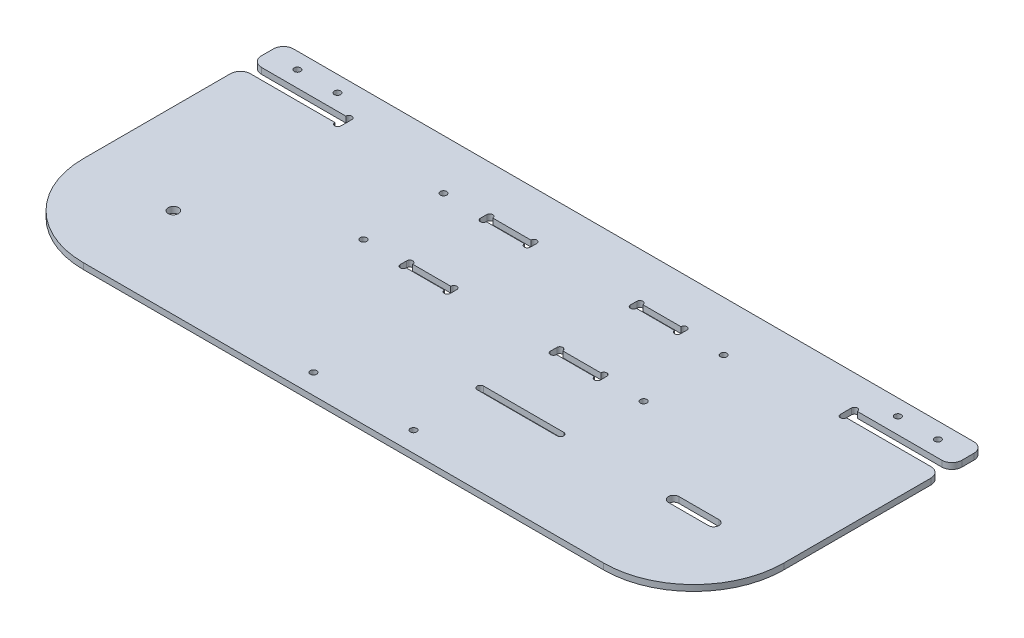
SolidWorks part; units mm, degrees
ref_plane "Front Plane" through (0, 0, 0) normal (0, 0, 1) x (1, 0, 0)
ref_plane "Top Plane" through (0, 0, 0) normal (0, 1, 0) x (1, 0, 0)
ref_plane "Right Plane" through (0, 0, 0) normal (1, 0, 0) x (0, 0, -1)
sketch "Sketch1" plane through (0, 0, 0) normal (0, 1, 0) x (1, 0, 0)
  line L0 (0, 0) -> (260, 0) construction
  line L5 (0, 45) -> (260, 45)
  line L6 (0, -45) -> (260, -45)
  line L7 (270, 0) -> (250, 0) construction
  line L8 (270, -2.6) -> (250, -2.6)
  line L9 (270, 2.6) -> (250, 2.6)
  line L11 (-45, 0) -> (305, 0) construction
  line L12 (-45, 0) -> (-45, 100)
  line L13 (-45, 100) -> (305, 100)
  line L14 (305, 0) -> (305, 100)
  arc A0 (0, 45) -> (0, -45) centre (0, 0) ccw
  arc A1 (260, -45) -> (260, 45) centre (260, 0) ccw
  circle A2 centre (0, 0) radius 2.6
  arc A4 (270, -2.6) -> (270, 2.6) centre (270, 0) ccw
  arc A5 (250, 2.6) -> (250, -2.6) centre (250, 0) ccw
  point P2 (130, 0)
  point P12 (260, 0)
  dimension "D2" = 45
  dimension "D3" = 5.2
  dimension "D1" = 260
  dimension "D4" = 20
  dimension "D5" = 100
  dimension "D6" = 270
extrude "Boss-Extrude1" add sketch "Sketch1" along normal blind 3 contours L6 A1 L5 A0 A5 L9 A4 L8 A2 | A1 L14 L13 L12 A0 L5
sketch "Sketch2" plane through (0, 0, 0) normal (0, -1, 0) x (1, 0, 0)
  line L0 (130, 45) -> (130, -100) construction
  line L1 (80, -73.4) -> (105, -73.4)
  line L2 (80, -73.4) -> (80, -76.6)
  line L3 (80, -76.6) -> (105, -76.6)
  line L4 (105, -73.4) -> (105, -76.6)
  line L5 (0, 45) -> (260, 45) construction
  line L6 (-45, -100) -> (305, -100) construction
  line L7 (-45, -75) -> (305, -75) construction
  line L8 (-45, 0) -> (-45, -100) construction
  line L9 (305, 0) -> (305, -100) construction
  line L10 (81.5, -73.4) -> (81.5, -76.6) construction
  line L11 (83, -73.4) -> (83, -76.6)
  line L12 (80, -73.4) -> (80, -76.6)
  line L13 (103.5, -73.4) -> (103.5, -76.6) construction
  line L14 (105, -73.4) -> (105, -76.6)
  line L15 (102, -73.4) -> (102, -76.6)
  line L16 (-45, -55) -> (305, -55) construction
  line L17 (156.5, -73.4) -> (156.5, -76.6) construction
  line L18 (155, -73.4) -> (155, -76.6)
  line L19 (158, -73.4) -> (158, -76.6)
  line L20 (180, -76.6) -> (155, -76.6)
  line L21 (180, -73.4) -> (155, -73.4)
  line L22 (178.5, -73.4) -> (178.5, -76.6) construction
  line L23 (177, -73.4) -> (177, -76.6)
  line L24 (180, -73.4) -> (180, -76.6)
  line L25 (180, -33.4) -> (155, -33.4)
  line L26 (81.5, -36.6) -> (81.5, -33.4) construction
  line L27 (83, -36.6) -> (83, -33.4)
  line L28 (80, -36.6) -> (80, -33.4)
  line L29 (80, -33.4) -> (105, -33.4)
  line L30 (103.5, -36.6) -> (103.5, -33.4) construction
  line L31 (105, -36.6) -> (105, -33.4)
  line L32 (102, -36.6) -> (102, -33.4)
  line L33 (80, -36.6) -> (105, -36.6)
  line L34 (156.5, -36.6) -> (156.5, -33.4) construction
  line L35 (155, -36.6) -> (155, -33.4)
  line L36 (158, -36.6) -> (158, -33.4)
  line L37 (180, -36.6) -> (155, -36.6)
  line L38 (178.5, -36.6) -> (178.5, -33.4) construction
  line L39 (177, -36.6) -> (177, -33.4)
  line L40 (180, -36.6) -> (180, -33.4)
  line L41 (-45, -92) -> (305, -92) construction
  arc A0 (83, -73.4) -> (80, -73.4) centre (81.5, -73.4) ccw
  arc A1 (80, -76.6) -> (83, -76.6) centre (81.5, -76.6) ccw
  arc A2 (105, -73.4) -> (102, -73.4) centre (103.5, -73.4) ccw
  arc A3 (102, -76.6) -> (105, -76.6) centre (103.5, -76.6) ccw
  arc A4 (155, -73.4) -> (158, -73.4) centre (156.5, -73.4) cw
  arc A5 (158, -76.6) -> (155, -76.6) centre (156.5, -76.6) cw
  arc A6 (177, -73.4) -> (180, -73.4) centre (178.5, -73.4) cw
  arc A7 (180, -76.6) -> (177, -76.6) centre (178.5, -76.6) cw
  arc A8 (83, -36.6) -> (80, -36.6) centre (81.5, -36.6) cw
  arc A9 (80, -33.4) -> (83, -33.4) centre (81.5, -33.4) cw
  arc A10 (105, -36.6) -> (102, -36.6) centre (103.5, -36.6) cw
  arc A11 (102, -33.4) -> (105, -33.4) centre (103.5, -33.4) cw
  arc A12 (155, -36.6) -> (158, -36.6) centre (156.5, -36.6) ccw
  arc A13 (158, -33.4) -> (155, -33.4) centre (156.5, -33.4) ccw
  arc A14 (177, -36.6) -> (180, -36.6) centre (178.5, -36.6) ccw
  arc A15 (180, -33.4) -> (177, -33.4) centre (178.5, -33.4) ccw
  circle A16 centre (-30, -92) radius 1.6
  circle A17 centre (-10, -92) radius 1.6
  circle A18 centre (60, -75) radius 1.6
  circle A19 centre (200, -75) radius 1.6
  circle A20 centre (290, -92) radius 1.6
  circle A21 centre (270, -92) radius 1.6
  circle A22 centre (200, -35) radius 1.6
  circle A23 centre (60, -35) radius 1.6
  point P16 (80, -75)
  point P19 (81.5, -75)
  point P24 (103.5, -75)
  point P35 (156.5, -75)
  point P46 (178.5, -75)
  point P53 (81.5, -35)
  point P62 (103.5, -35)
  point P70 (156.5, -35)
  point P78 (178.5, -35)
  dimension "D5" = 1.5
  dimension "D8" = 3.2
  dimension "D1" = 25
  dimension "D2" = 3.2
  dimension "D3" = 25
  dimension "D4" = 120
  dimension "D6" = 20
  dimension "D7" = 8
  dimension "D9" = 20
  dimension "D10" = 15
  dimension "D11" = 20
extrude "Cut-Extrude1" cut sketch "Sketch2" against normal blind 10 contours L28 L33 L27 L29 | A9 L29 | A8 L33 | L27 L33 L32 L29 | A11 L29 | L32 L33 L31 L29 | A10 L33 | L1 A0 | L11 L1 L2 L3 | L15 L1 L11 L3 | L3 A1 | L1 A2 | L1 L15 L3 L4 | L3 A3 | L25 A13 | L37 L36 L25 L35 | L37 A12 | L37 L39 L25 L36 | L25 A15 | L37 L40 L25 L39 | L37 A14 | A4 L21 | L19 L21 L18 L20 | A5 L20 | L23 L21 L19 L20 | A6 L21 | L24 L21 L23 L20 | A7 L20 | A19 | A20 | A21 | A23 | A18 | A17 | A16 | A22
fillet "Fillet1" radius 5 2 edges at (305, 1.5, -100) (-45, 1.5, -100)
sketch "Sketch3" plane through (0, 0, 0) normal (0, -1, 0) x (1, 0, 0)
  line L0 (270, 0) -> (0, 0) construction
  line L1 (193.4, 0) -> (153.4, 0) construction
  line L2 (193.4, -1.6) -> (153.4, -1.6)
  line L3 (193.4, 1.6) -> (153.4, 1.6)
  line L6 (155, -36.6) -> (155, 45) construction
  line L7 (0, 45) -> (260, 45) construction
  line L8 (105, 35) -> (155, 35) construction
  line L9 (130, -100) -> (130, 45) construction
  line L10 (-40, -100) -> (300, -100) construction
  arc A0 (193.4, -1.6) -> (193.4, 1.6) centre (193.4, 0) ccw
  arc A1 (153.4, 1.6) -> (153.4, -1.6) centre (153.4, 0) ccw
  circle A2 centre (105, 35) radius 1.6
  circle A4 centre (155, 35) radius 1.6
  point P6 (173.4, 0)
  point P19 (130, 35)
  dimension "D3" = 10
  dimension "D4" = 3.2
  dimension "D1" = 3.2
  dimension "D2" = 40
  dimension "D5" = 25
extrude "Cut-Extrude2" cut sketch "Sketch3" against normal through all
sketch "Sketch4" plane through (0, 3, 0) normal (0, 1, 0) x (1, 0, 0)
  line L0 (-45, 0) -> (-45, 95) construction
  line L1 (-45, 84) -> (5.2, 84)
  line L2 (-45, 84) -> (-45, 78.5)
  line L3 (-45, 78.5) -> (5.2, 78.5)
  line L4 (5.2, 84) -> (5.2, 78.5)
  line L5 (130, 100) -> (130, -45) construction
  line L6 (-40, 100) -> (300, 100) construction
  line L7 (0, -45) -> (260, -45) construction
  line L8 (3.7, 84) -> (3.7, 78.5) construction
  line L9 (5.2, 84) -> (5.2, 78.5)
  line L10 (2.2, 84) -> (2.2, 78.5)
  line L11 (256.3, 84) -> (256.3, 78.5) construction
  line L12 (254.8, 84) -> (254.8, 78.5)
  line L13 (257.8, 84) -> (257.8, 78.5)
  line L14 (305, 84) -> (305, 78.5)
  line L15 (305, 78.5) -> (254.8, 78.5)
  line L16 (305, 84) -> (254.8, 84)
  arc A0 (5.2, 84) -> (2.2, 84) centre (3.7, 84) ccw
  arc A1 (2.2, 78.5) -> (5.2, 78.5) centre (3.7, 78.5) ccw
  arc A2 (254.8, 84) -> (257.8, 84) centre (256.3, 84) cw
  arc A3 (257.8, 78.5) -> (254.8, 78.5) centre (256.3, 78.5) cw
  point P14 (3.7, 81.25)
  point P21 (256.3, 81.25)
  dimension "D4" = 1.5
  dimension "D1" = 16
  dimension "D2" = 5.5
  dimension "D3" = 50.2
extrude "Cut-Extrude3" cut sketch "Sketch4" against normal through all contours L10 L1 L2 L3 | L1 L10 L3 L4 | L1 A0 | L3 A1 | A2 L16 | L13 L16 L12 L15 | A3 L15 | L14 L16 L13 L15
fillet "Fillet2" radius 5 4 edges at (305, 1.5, -78.5) (305, 1.5, -84) (-45, 1.5, -78.5) (-45, 1.5, -84)
